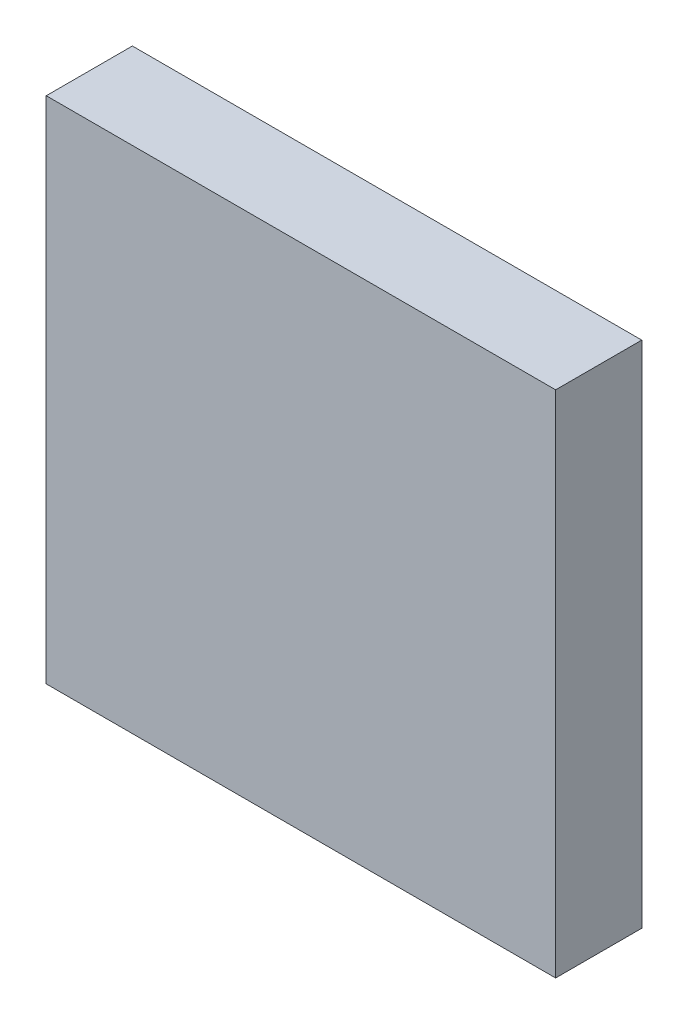
SolidWorks part; units mm, degrees
ref_plane "Ön Düzlem" through (0, 0, 0) normal (0, 0, 1) x (1, 0, 0)
ref_plane "Üst Düzlem" through (0, 0, 0) normal (0, 1, 0) x (1, 0, 0)
ref_plane "Sağ Düzlem" through (0, 0, 0) normal (1, 0, 0) x (0, 0, -1)
sketch "Sketch1" plane through (0, 0, 0) normal (0, 0, 1) x (1, 0, 0)
  line L1 (-145.2912, -146.8188) -> (70.6088, -146.8188)
  line L2 (-145.2912, -146.8188) -> (-145.2912, 69.0812)
  line L3 (-145.2912, 69.0812) -> (70.6088, 69.0812)
  line L4 (70.6088, -146.8188) -> (70.6088, 69.0812)
  line L5 (-145.2912, -146.8188) -> (70.6088, 69.0812) construction
  line L6 (-145.2912, 69.0812) -> (70.6088, -146.8188) construction
  point P0 (-37.3412, -38.8688)
  dimension "D1" = 215.9
extrude "Boss-Extrude1" add sketch "Sketch1" along normal blind 36.5
